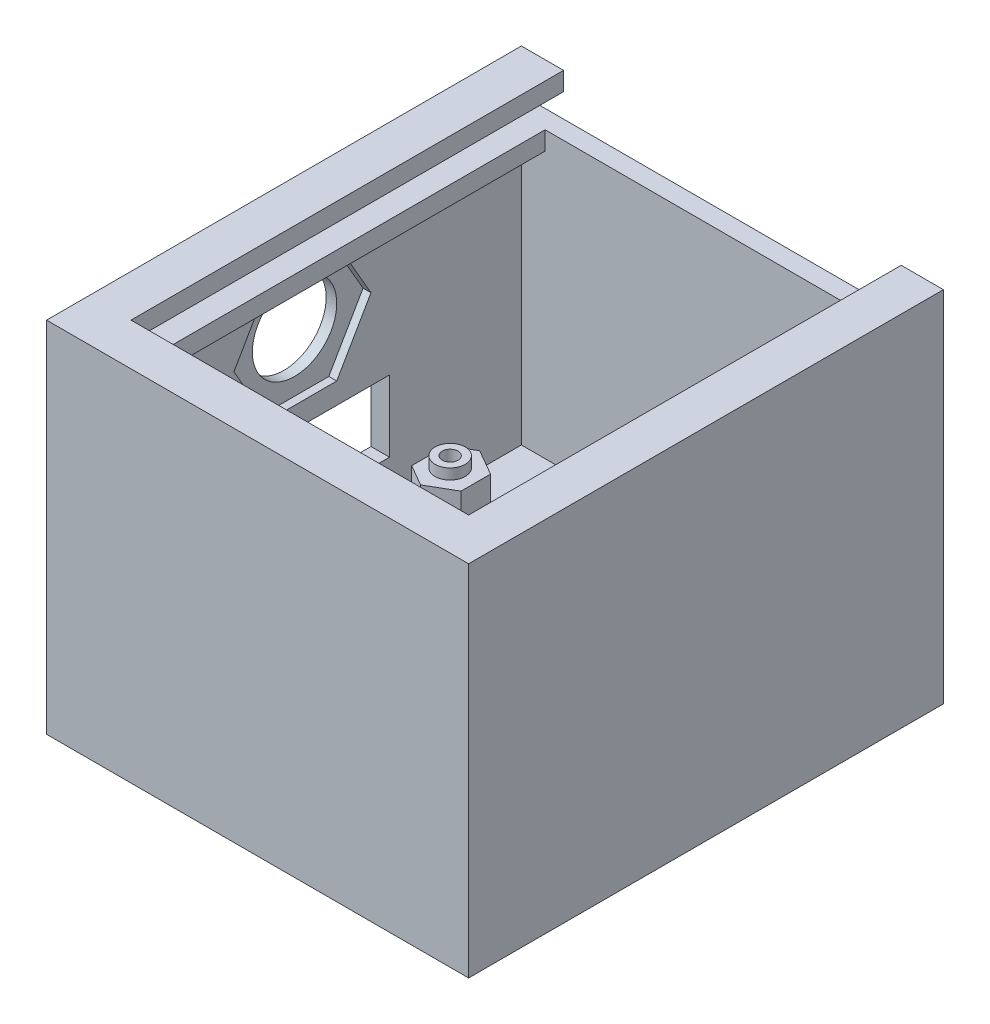
SolidWorks part; units mm, degrees
ref_plane "Front Plane" through (0, 0, 0) normal (0, 0, 1) x (1, 0, 0)
ref_plane "Top Plane" through (0, 0, 0) normal (0, 1, 0) x (1, 0, 0)
ref_plane "Right Plane" through (0, 0, 0) normal (1, 0, 0) x (0, 0, -1)
sketch "Sketch1" plane through (0, 0, 0) normal (0, 1, 0) x (1, 0, 0)
  line L1 (-40, -45) -> (40, -45)
  line L2 (-40, -45) -> (-40, 45)
  line L3 (-40, 45) -> (40, 45)
  line L4 (40, -45) -> (40, 45)
  line L5 (-40, -45) -> (40, 45) construction
  line L6 (-40, 45) -> (40, -45) construction
  point P0 (0, 0)
  dimension "D1" = 80
  dimension "D2" = 90
extrude "Boss-Extrude1" add sketch "Sketch1" along normal blind 6
sketch "Sketch4" plane through (0, 6, 0) normal (0, 1, 0) x (1, 0, 0)
  line L0 (40, -45) -> (40, 45) construction
  line L1 (-40, 45) -> (40, 45)
  line L2 (-40, 45) -> (-40, -45)
  line L3 (-40, -45) -> (40, -45)
  line L4 (40, 45) -> (40, -45)
  line L5 (-36.5, 41.5) -> (36.5, 41.5)
  line L6 (-36.5, 41.5) -> (-36.5, -41.5)
  line L7 (-36.5, -41.5) -> (36.5, -41.5)
  line L8 (36.5, 41.5) -> (36.5, -41.5)
  dimension "D1" = 3.5
  dimension "D2" = 3.5
  dimension "D3" = 3.5
  dimension "D4" = 3.5
extrude "Boss-Extrude2" add sketch "Sketch4" along normal blind 54 contours L2 L1 L4 L3 | L6 L5 L8 L7
sketch "Sketch5" plane through (0, 6, 0) normal (0, 1, 0) x (1, 0, 0)
  line L0 (-40, 45) -> (40, 45) construction
  line L1 (-36.5, 41.5) -> (-36.5, -41.5) construction
  line L2 (-36.5, 41.5) -> (-36.5, -41.5) construction
  circle A0 centre (-32.5, 24) radius 1.5
  circle A1 centre (-32.5, -24) radius 1.5
  circle A2 centre (2.8, 14) radius 1.5
  circle A3 centre (2.8, -14) radius 1.5
  dimension "D1" = 3
  dimension "D4" = 3
  dimension "D9" = 3
  dimension "D10" = 3
  dimension "D2" = 21
  dimension "D3" = 4
  dimension "D5" = 48
  dimension "D6" = 4
  dimension "D7" = 28
  dimension "D8" = 39.3
  dimension "D11" = 10
sketch "Sketch6" plane through (0, 6, 0) normal (0, 1, 0) x (1, 0, 0)
  line L0 (-40, 45) -> (-40, -45) construction
  line L1 (-40, 45) -> (40, 45) construction
  line L2 (-40, -45) -> (40, -45) construction
  line L3 (40, 45) -> (40, -45) construction
  circle A0 centre (-20, 25) radius 4.05
  circle A1 centre (-20, -25) radius 4.05
  circle A2 centre (20, -25) radius 5
  dimension "D2" = 8.1
  dimension "D3" = 8.1
  dimension "D4" = 20
  dimension "D5" = 20
  dimension "D8" = 10
  dimension "D1" = 20
  dimension "D6" = 20
  dimension "D7" = 20
extrude "Cut-Extrude1" cut sketch "Sketch6" against normal blind 40
sketch "Sketch7" plane through (0, 6, 0) normal (0, 1, 0) x (1, 0, 0)
  circle A0 centre (-20, 25) radius 7
  circle A1 centre (-20, -25) radius 7
  dimension "D1" = 14
  dimension "D2" = 14
extrude "Cut-Extrude2" cut sketch "Sketch7" against normal blind 2.8
sketch "Sketch8" plane through (0, 6, 0) normal (0, 1, 0) x (1, 0, 0)
  line L0 (-36.5, 41.5) -> (-36.5, -41.5) construction
  line L1 (-29.65, 25.6454) -> (-32.5, 27.2909)
  line L2 (-32.5, 27.2909) -> (-35.35, 25.6454)
  line L3 (-35.35, 25.6454) -> (-35.35, 22.3546)
  line L4 (-35.35, 22.3546) -> (-32.5, 20.7091)
  line L5 (-32.5, 20.7091) -> (-29.65, 22.3546)
  line L6 (-29.65, 22.3546) -> (-29.65, 25.6454)
  line L7 (-36.5, 41.5) -> (-36.5, -41.5) construction
  line L8 (-29.65, -22.3546) -> (-32.5, -20.7091)
  line L9 (-32.5, -20.7091) -> (-35.35, -22.3546)
  line L10 (-35.35, -22.3546) -> (-35.35, -25.6454)
  line L11 (-35.35, -25.6454) -> (-32.5, -27.2909)
  line L12 (-32.5, -27.2909) -> (-29.65, -25.6454)
  line L13 (-29.65, -25.6454) -> (-29.65, -22.3546)
  line L14 (5.65, -12.3546) -> (2.8, -10.7091)
  line L15 (2.8, -10.7091) -> (-0.05, -12.3546)
  line L16 (-0.05, -12.3546) -> (-0.05, -15.6454)
  line L17 (-0.05, -15.6454) -> (2.8, -17.2909)
  line L18 (2.8, -17.2909) -> (5.65, -15.6454)
  line L19 (5.65, -15.6454) -> (5.65, -12.3546)
  line L20 (5.65, 15.6454) -> (2.8, 17.2909)
  line L21 (2.8, 17.2909) -> (-0.05, 15.6454)
  line L22 (-0.05, 15.6454) -> (-0.05, 12.3546)
  line L23 (-0.05, 12.3546) -> (2.8, 10.7091)
  line L24 (2.8, 10.7091) -> (5.65, 12.3546)
  line L25 (5.65, 12.3546) -> (5.65, 15.6454)
  circle A0 centre (-32.5, 24) radius 2.85 construction
  circle A1 centre (-32.5, -24) radius 2.85 construction
  circle A2 centre (2.8, -14) radius 2.85 construction
  circle A3 centre (2.8, 14) radius 2.85 construction
  point P40 (-33.925, -21.5318)
  dimension "D2" = 5.7
  dimension "D1" = 5.7
  dimension "D3" = 5.7
  dimension "D4" = 5.7
sketch "Sketch10" plane through (0, 6, 0) normal (0, 1, 0) x (1, 0, 0)
  line L1 (-32.5, 29.6003) -> (-37.35, 26.8001)
  line L2 (-37.35, 26.8001) -> (-37.35, 21.1999)
  line L3 (-37.35, 21.1999) -> (-32.5, 18.3997)
  line L4 (-32.5, 18.3997) -> (-27.65, 21.1999)
  line L5 (-27.65, 21.1999) -> (-27.65, 26.8001)
  line L6 (-27.65, 26.8001) -> (-32.5, 29.6003)
  line L7 (2.8, 19.6003) -> (-2.05, 16.8001)
  line L8 (-2.05, 16.8001) -> (-2.05, 11.1999)
  line L9 (-2.05, 11.1999) -> (2.8, 8.3997)
  line L10 (2.8, 8.3997) -> (7.65, 11.1999)
  line L11 (7.65, 11.1999) -> (7.65, 16.8001)
  line L12 (7.65, 16.8001) -> (2.8, 19.6003)
  line L13 (2.8, -8.3997) -> (-2.05, -11.1999)
  line L14 (-2.05, -11.1999) -> (-2.05, -16.8001)
  line L15 (-2.05, -16.8001) -> (2.8, -19.6003)
  line L16 (2.8, -19.6003) -> (7.65, -16.8001)
  line L17 (7.65, -16.8001) -> (7.65, -11.1999)
  line L18 (7.65, -11.1999) -> (2.8, -8.3997)
  line L19 (-27.65, -21.1999) -> (-32.5, -18.3997)
  line L20 (-32.5, -18.3997) -> (-37.35, -21.1999)
  line L21 (-37.35, -21.1999) -> (-37.35, -26.8001)
  line L22 (-37.35, -26.8001) -> (-32.5, -29.6003)
  line L23 (-32.5, -29.6003) -> (-27.65, -26.8001)
  line L24 (-27.65, -26.8001) -> (-27.65, -21.1999)
  line L25 (-36.5, 41.5) -> (-36.5, -41.5) construction
  line L26 (-36.5, 41.5) -> (-36.5, -41.5) construction
  line L27 (-32.5, 20.7091) -> (-29.65, 22.3546) construction
  line L28 (-32.5, -27.2909) -> (-29.65, -25.6454) construction
  line L29 (2.8, -17.2909) -> (5.65, -15.6454) construction
  line L30 (2.8, 10.7091) -> (5.65, 12.3546) construction
  circle A0 centre (-32.5, 24) radius 4.85 construction
  circle A1 centre (2.8, 14) radius 4.85 construction
  circle A2 centre (2.8, -14) radius 4.85 construction
  circle A3 centre (-32.5, -24) radius 4.85 construction
  dimension "D1" = 2
  dimension "D2" = 2
  dimension "D3" = 2
  dimension "D4" = 2
extrude "Boss-Extrude3" add sketch "Sketch10" along normal blind 7
sketch "Sketch11" plane through (0, 13, 0) normal (0, 1, 0) x (1, 0, 0)
  circle A0 centre (-32.5, 24) radius 2.85
  circle A1 centre (2.8, 14) radius 2.85
  circle A2 centre (2.8, -14) radius 2.85
  circle A3 centre (-32.5, -24) radius 2.85
  dimension "D1" = 5.7
  dimension "D2" = 5.7
  dimension "D3" = 5.7
  dimension "D4" = 5.7
extrude "Boss-Extrude4" add sketch "Sketch11" along normal blind 2
extrude "Cut-Extrude3" cut sketch "Sketch5" against normal blind 6 and the other way blind 9
extrude "Cut-Extrude4" cut sketch "Sketch8" against normal through all and the other way blind 6
sketch "Sketch12" plane through (-36.5, 0, 0) normal (1, 0, 0) x (0, 0, -1)
  line L0 (45, 0) -> (-45, 0) construction
  line L1 (16.5, 16.5) -> (-16.5, 16.5)
  line L2 (16.5, 16.5) -> (16.5, 30)
  line L3 (16.5, 30) -> (-16.5, 30)
  line L4 (-16.5, 16.5) -> (-16.5, 30)
  line L5 (45, 60) -> (45, 0) construction
  dimension "D1" = 33
  dimension "D2" = 13.5
  dimension "16.5mm" = 16.5
  dimension "D4" = 28.5
extrude "Cut-Extrude6" cut sketch "Sketch12" against normal blind 3.5
sketch "Sketch15" plane through (-36.5, 0, 0) normal (1, 0, 0) x (0, 0, -1)
  line L0 (16.5, 30) -> (-16.5, 30) construction
  line L1 (-6.4952, 56.5) -> (-12.9904, 45.25)
  line L2 (-12.9904, 45.25) -> (-6.4952, 34)
  line L3 (-6.4952, 34) -> (6.4952, 34)
  line L4 (6.4952, 34) -> (12.9904, 45.25)
  line L5 (12.9904, 45.25) -> (6.4952, 56.5)
  line L6 (6.4952, 56.5) -> (-6.4952, 56.5)
  line L7 (45, 60) -> (45, 0) construction
  circle A1 centre (0, 45.25) radius 11.25 construction
  dimension "D1" = 22.5
  dimension "D2" = 45
  dimension "D3" = 4
sketch "Sketch17" plane through (-40, 0, 0) normal (-1, 0, 0) x (0, 0, 1)
  circle A0 centre (0, 45.25) radius 8
  dimension "D1" = 16
extrude "Cut-Extrude8" cut sketch "Sketch17" against normal blind 2
extrude "Cut-Extrude9" cut sketch "Sketch15" against normal blind 1.5
sketch "Sketch18" plane through (0, 15, 0) normal (0, 1, 0) x (1, 0, 0)
  line L1 (-35.5, 28) -> (7.8, 28)
  line L2 (-35.5, 28) -> (-35.5, -28)
  line L3 (-35.5, -28) -> (7.8, -28)
  line L4 (7.8, 28) -> (7.8, -28)
  circle A0 centre (-32.5, 24) radius 1.5 construction
  dimension "D1" = 4
  dimension "D2" = 3
  dimension "D3" = 56
  dimension "D4" = 43.3
sketch "Sketch19" plane through (0, 6, 0) normal (0, 1, 0) x (1, 0, 0)
  line L0 (0, -5.5) -> (0, 5.5) construction
  line L1 (-3.5, -5.5) -> (-3.5, 5.5)
  line L2 (3.5, -5.5) -> (3.5, 5.5)
  line L3 (40, 45) -> (40, -45) construction
  line L5 (-40, -45) -> (40, -45) construction
  arc A0 (-3.5, -5.5) -> (3.5, -5.5) centre (0, -5.5) ccw
  arc A1 (3.5, 5.5) -> (-3.5, 5.5) centre (0, 5.5) ccw
  point P2 (0, 0)
  dimension "D1" = 40
  dimension "D2" = 45
  dimension "D3" = 11
  dimension "D4" = 7
extrude "Cut-Extrude10" cut sketch "Sketch19" against normal blind 10
sketch "Sketch20" plane through (0, 0, -45) normal (0, 0, -1) x (-1, 0, 0)
  line L0 (40, 60) -> (-40, 60) construction
  line L1 (-40, 60) -> (-36.5, 60)
  line L4 (-36.5, 60) -> (-36.5, 64.5)
  line L5 (40, 60) -> (36.5, 60)
  line L8 (36.5, 60) -> (36.5, 64.5)
  line L9 (-36.5, 64.5) -> (-32, 64.5)
  line L11 (-40, 68) -> (-32, 68)
  line L12 (-32, 64.5) -> (-32, 68)
  line L13 (36.5, 64.5) -> (32, 64.5)
  line L15 (40, 68) -> (32, 68)
  line L16 (32, 64.5) -> (32, 68)
  line L17 (-40, 68) -> (-40, 60)
  line L18 (40, 68) -> (40, 60)
  dimension "D1" = 8
  dimension "D2" = 3.5
  dimension "D3" = 3.5
  dimension "D4" = 3.5
  dimension "D5" = 3.5
  dimension "D7" = 8
  dimension "D8" = 8
extrude "Boss-Extrude5" add sketch "Sketch20" against normal blind 90 separate body
sketch "Sketch21" plane through (40, 0, 0) normal (1, 0, 0) x (0, 0, -1)
  line L0 (-45, 68) -> (45, 68) construction
  line L1 (-45, 60) -> (-41.5, 60)
  line L2 (-45, 60) -> (-45, 68)
  line L3 (-45, 68) -> (-41.5, 68)
  line L4 (-41.5, 60) -> (-41.5, 68)
  dimension "D1" = 3.5
extrude "Boss-Extrude6" add sketch "Sketch21" against normal blind 80
sketch "Sketch22" plane through (0, 0, 41.5) normal (0, 0, -1) x (-1, 0, 0)
  line L0 (-40, 68) -> (-40, 0) construction
  line L5 (40, 68) -> (-40, 68)
  line L6 (40, 68) -> (40, 64.5)
  line L7 (40, 64.5) -> (-40, 64.5)
  line L8 (-40, 68) -> (-40, 64.5)
  dimension "D1" = 3.5
extrude "Boss-Extrude7" add sketch "Sketch22" along normal blind 4.5
sketch "Sketch24" plane through (0, 0, 45) normal (0, 0, 1) x (1, 0, 0)
  line L0 (-40, 0) -> (-40, 68) construction
  line L1 (-40, 60) -> (-32, 60)
  line L2 (-40, 60) -> (-40, 56.5)
  line L3 (-40, 56.5) -> (-32, 56.5)
  line L4 (40, 60) -> (40, 56.5)
  line L5 (40, 68) -> (40, 0) construction
  line L6 (-40, 68) -> (40, 68) construction
  line L7 (32, 60) -> (40, 60)
  line L9 (-32, 60) -> (-32, 56.5)
  line L11 (32, 60) -> (32, 56.5)
  line L12 (32, 56.5) -> (40, 56.5)
  dimension "D1" = 3.5
  dimension "D2" = 8
  dimension "D3" = 8
  dimension "D4" = 8
extrude "Boss-Extrude8" add sketch "Sketch24" against normal blind 90
